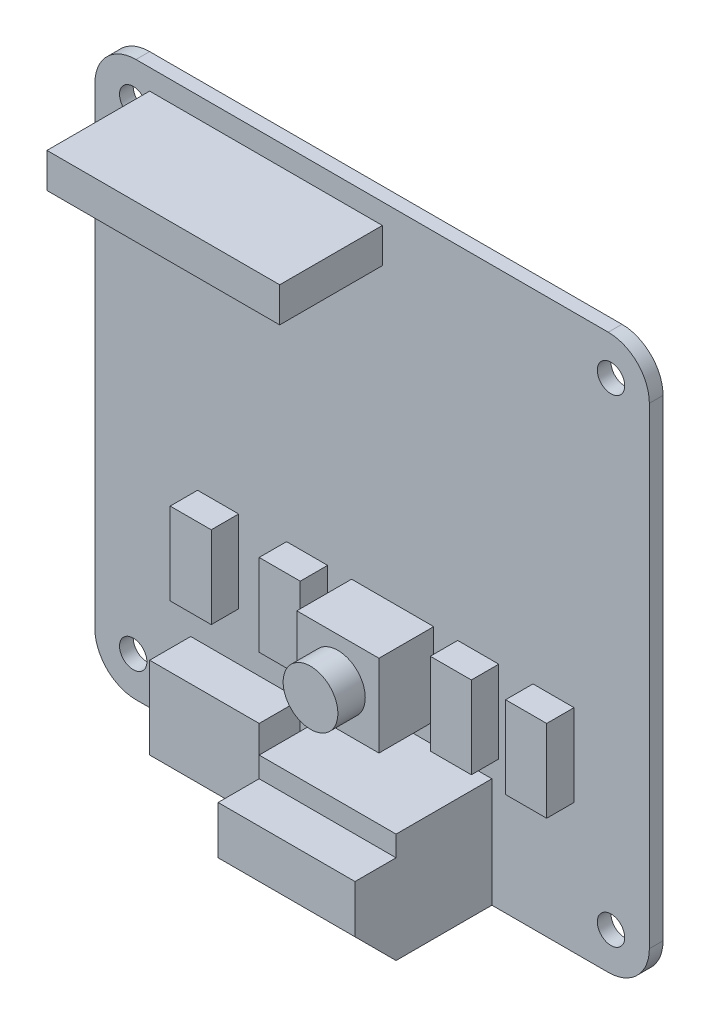
SolidWorks part; units mm, degrees
ref_plane "Plan de face" through (0, 0, 0) normal (0, 0, 1) x (1, 0, 0)
ref_plane "Plan de dessus" through (0, 0, 0) normal (0, 1, 0) x (1, 0, 0)
ref_plane "Plan de droite" through (0, 0, 0) normal (1, 0, 0) x (0, 0, -1)
sketch "Esquisse1" plane through (0, 0, 0) normal (0, 0, 1) x (1, 0, 0)
  line L0 (2.8, 37.7) -> (37.7, 37.7) construction
  line L1 (0, 0) -> (40.5, 0)
  line L2 (0, 0) -> (0, 40.5)
  line L3 (0, 40.5) -> (40.5, 40.5)
  line L4 (40.5, 0) -> (40.5, 40.5)
  line L5 (37.7, 2.8) -> (37.7, 37.7) construction
  line L6 (2.8, 2.8) -> (37.7, 2.8) construction
  line L7 (2.8, 2.8) -> (2.8, 37.7) construction
  circle A0 centre (37.7, 37.7) radius 1
  circle A1 centre (37.7, 2.8) radius 1
  circle A2 centre (2.8, 2.8) radius 1
  circle A3 centre (2.8, 37.7) radius 1
  dimension "D4" = 2
  dimension "D1" = 40.5
  dimension "D2" = 40.5
  dimension "D3" = 2.8
extrude "Boss.-Extru.1" add sketch "Esquisse1" along normal blind 1
fillet "Congé1" radius 3 4 edges at (0, 0, 0.5) (0, 40.5, 0.5) (40.5, 0, 0.5) (40.5, 40.5, 0.5)
sketch "Esquisse2" plane through (0, 0, 1) normal (0, 0, 1) x (1, 0, 0)
  line L0 (3, 0) -> (37.5, 0) construction
  line L1 (29, 0) -> (19, 0)
  line L2 (29, 0) -> (29, 8)
  line L3 (29, 8) -> (19, 8)
  line L4 (19, 0) -> (19, 8)
  line L5 (40.5, 3) -> (40.5, 37.5) construction
  dimension "D1" = 11.5
  dimension "D2" = 10
  dimension "D3" = 8
extrude "Boss.-Extru.2" add sketch "Esquisse2" along normal blind 10
sketch "Esquisse3" plane through (29, 0, 0) normal (1, 0, 0) x (0, 0, -1)
  line L0 (-8, 0) -> (-11, 3)
  line L1 (-11, 0) -> (-1, 0) construction
  line L2 (-11, 0) -> (-11, 8) construction
  line L3 (-11, 3) -> (-11, 0)
  line L4 (-11, 0) -> (-8, 0)
  line L6 (-11, 6.5) -> (-8, 6.5)
  line L7 (-8, 6.5) -> (-8, 8)
  line L8 (-11, 8) -> (-1, 8) construction
  line L9 (-8, 8) -> (-11, 8)
  line L10 (-11, 8) -> (-11, 6.5)
  dimension "D1" = 5
  dimension "D2" = 7
  dimension "D3" = 1.5
  dimension "D4" = 3
extrude "Enlèv. mat.-Extru.1" cut sketch "Esquisse3" against normal blind 10
sketch "Esquisse4" plane through (0, 0, 1) normal (0, 0, 1) x (1, 0, 0)
  line L0 (3, 0) -> (19, 0) construction
  line L1 (15, 0) -> (7, 0)
  line L2 (15, 0) -> (15, 6)
  line L3 (15, 6) -> (7, 6)
  line L4 (7, 0) -> (7, 6)
  line L5 (19, 8) -> (19, 0) construction
  dimension "D1" = 4
  dimension "D2" = 8
  dimension "D3" = 6
extrude "Boss.-Extru.3" add sketch "Esquisse4" along normal blind 3
sketch "Esquisse5" plane through (0, 0, 1) normal (0, 0, 1) x (1, 0, 0)
  line L0 (0, 12.5) -> (40.5, 12.5) construction
  line L1 (0, 37.5) -> (0, 3) construction
  line L2 (40.5, 3) -> (40.5, 37.5) construction
  line L3 (3, 0) -> (7, 0) construction
  line L4 (10.5, 15.5) -> (7.5, 15.5)
  line L5 (10.5, 15.5) -> (10.5, 9.5)
  line L6 (10.5, 9.5) -> (7.5, 9.5)
  line L7 (7.5, 15.5) -> (7.5, 9.5)
  line L8 (10.5, 15.5) -> (7.5, 9.5) construction
  line L9 (10.5, 9.5) -> (7.5, 15.5) construction
  line L10 (17, 15.5) -> (14, 15.5)
  line L11 (17, 15.5) -> (17, 9.5)
  line L12 (17, 9.5) -> (14, 9.5)
  line L13 (14, 15.5) -> (14, 9.5)
  line L14 (17, 15.5) -> (14, 9.5) construction
  line L15 (17, 9.5) -> (14, 15.5) construction
  line L16 (29.5, 15.5) -> (26.5, 15.5)
  line L17 (29.5, 15.5) -> (29.5, 9.5)
  line L18 (29.5, 9.5) -> (26.5, 9.5)
  line L19 (26.5, 15.5) -> (26.5, 9.5)
  line L20 (29.5, 15.5) -> (26.5, 9.5) construction
  line L21 (29.5, 9.5) -> (26.5, 15.5) construction
  line L22 (35, 15.5) -> (32, 15.5)
  line L23 (35, 15.5) -> (35, 9.5)
  line L24 (35, 9.5) -> (32, 9.5)
  line L25 (32, 15.5) -> (32, 9.5)
  line L26 (35, 15.5) -> (32, 9.5) construction
  line L27 (35, 9.5) -> (32, 15.5) construction
  point P6 (9, 12.5)
  point P11 (15.5, 12.5)
  point P16 (28, 12.5)
  point P21 (33.5, 12.5)
  point P26 (9, 15.5)
  dimension "D1" = 6
  dimension "D2" = 3
  dimension "D3" = 9
  dimension "D4" = 6.5
  dimension "D5" = 5.5
  dimension "D6" = 7
  dimension "D7" = 12.5
extrude "Boss.-Extru.4" add sketch "Esquisse5" along normal blind 2
sketch "Esquisse6" plane through (0, 0, 1) normal (0, 0, 1) x (1, 0, 0)
  line L0 (17, 12.5) -> (26.5, 12.5) construction
  line L1 (17, 9.5) -> (17, 15.5) construction
  line L2 (26.5, 15.5) -> (26.5, 9.5) construction
  line L4 (18.75, 9.5) -> (24.75, 9.5)
  line L5 (18.75, 9.5) -> (18.75, 15.5)
  line L6 (18.75, 15.5) -> (24.75, 15.5)
  line L7 (24.75, 9.5) -> (24.75, 15.5)
  line L8 (18.75, 9.5) -> (24.75, 15.5) construction
  line L9 (18.75, 15.5) -> (24.75, 9.5) construction
  point P6 (21.75, 12.5)
  dimension "D1" = 6
  dimension "D2" = 6
extrude "Boss.-Extru.5" add sketch "Esquisse6" along normal blind 4
sketch "Esquisse7" plane through (0, 0, 5) normal (0, 0, 1) x (1, 0, 0)
  line L0 (18.75, 9.5) -> (24.75, 15.5) construction
  circle A0 centre (21.75, 12.5) radius 2
  dimension "D1" = 4
extrude "Boss.-Extru.6" add sketch "Esquisse7" along normal blind 2
sketch "Esquisse8" plane through (0, 0, 1) normal (0, 0, 1) x (1, 0, 0)
  line L0 (37.5, 40.5) -> (3, 40.5) construction
  line L1 (21, 36.46) -> (4, 36.46)
  line L2 (21, 36.46) -> (21, 39)
  line L3 (21, 39) -> (4, 39)
  line L4 (4, 36.46) -> (4, 39)
  line L5 (21, 36.46) -> (4, 39) construction
  line L6 (21, 39) -> (4, 36.46) construction
  line L7 (0, 37.5) -> (0, 3) construction
  point P0 (12.5, 37.73)
  dimension "D1" = 1.5
  dimension "D2" = 4
  dimension "D3" = 2.54
  dimension "D4" = 17
extrude "Boss.-Extru.7" add sketch "Esquisse8" along normal blind 7.5
